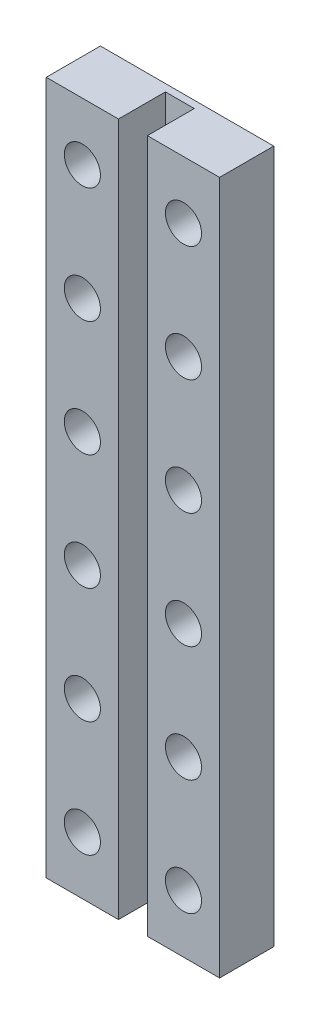
SolidWorks part; units mm, degrees
ref_plane "Plan de face" through (0, 0, 0) normal (0, 0, 1) x (1, 0, 0)
ref_plane "Plan de dessus" through (0, 0, 0) normal (0, 1, 0) x (1, 0, 0)
ref_plane "Plan de droite" through (0, 0, 0) normal (1, 0, 0) x (0, 0, -1)
sketch "Esquisse1" plane through (0, 0, 0) normal (0, 1, 0) x (1, 0, 0)
  line L0 (-2, -3.75) -> (-2, 2.75)
  line L1 (12, 3.75) -> (-12, 3.75)
  line L2 (12, 3.75) -> (12, -3.75)
  line L3 (12, -3.75) -> (2, -3.75)
  line L4 (-12, 3.75) -> (-12, -3.75)
  line L5 (12, 3.75) -> (-12, -3.75) construction
  line L6 (12, -3.75) -> (-12, 3.75) construction
  line L7 (-2, 2.75) -> (2, 2.75)
  line L8 (2, 2.75) -> (2, -3.75)
  line L9 (-2, 2.75) -> (2, -3.75) construction
  line L10 (0, 1.5046) -> (0, -2.3161) construction
  line L11 (-2, -3.75) -> (-12, -3.75)
  point P0 (0, 0)
  point P8 (0, -0.5)
  dimension "D1" = 7.5
  dimension "D2" = 24
  dimension "D3" = 1
  dimension "D4" = 10
extrude "BASE" add sketch "Esquisse1" against normal blind 96
sketch "Esquisse2" plane through (0, 0, 3.75) normal (0, 0, 1) x (1, 0, 0)
  line L0 (-7, 0) -> (-7, -38.4741) construction
  line L1 (-12, 0) -> (-2, 0) construction
  line L2 (-7, -5.5) -> (-4.873, -5.5) construction
  circle A0 centre (-7, -8) radius 2.5
  circle A1 centre (7, -8) radius 2.5
  circle A2 centre (7, -24) radius 2.5
  circle A3 centre (7, -40) radius 2.5
  circle A4 centre (7, -56) radius 2.5
  circle A5 centre (7, -72) radius 2.5
  circle A6 centre (7, -88) radius 2.5
  circle A11 centre (-7, -24) radius 2.5
  circle A12 centre (-7, -40) radius 2.5
  circle A13 centre (-7, -56) radius 2.5
  circle A14 centre (-7, -72) radius 2.5
  circle A15 centre (-7, -88) radius 2.5
  dimension "D2" = 5
  dimension "D1" = 5.5
  dimension "D3" = 2
  dimension "D4" = 6
extrude "TROU" cut sketch "Esquisse2" against normal through all
